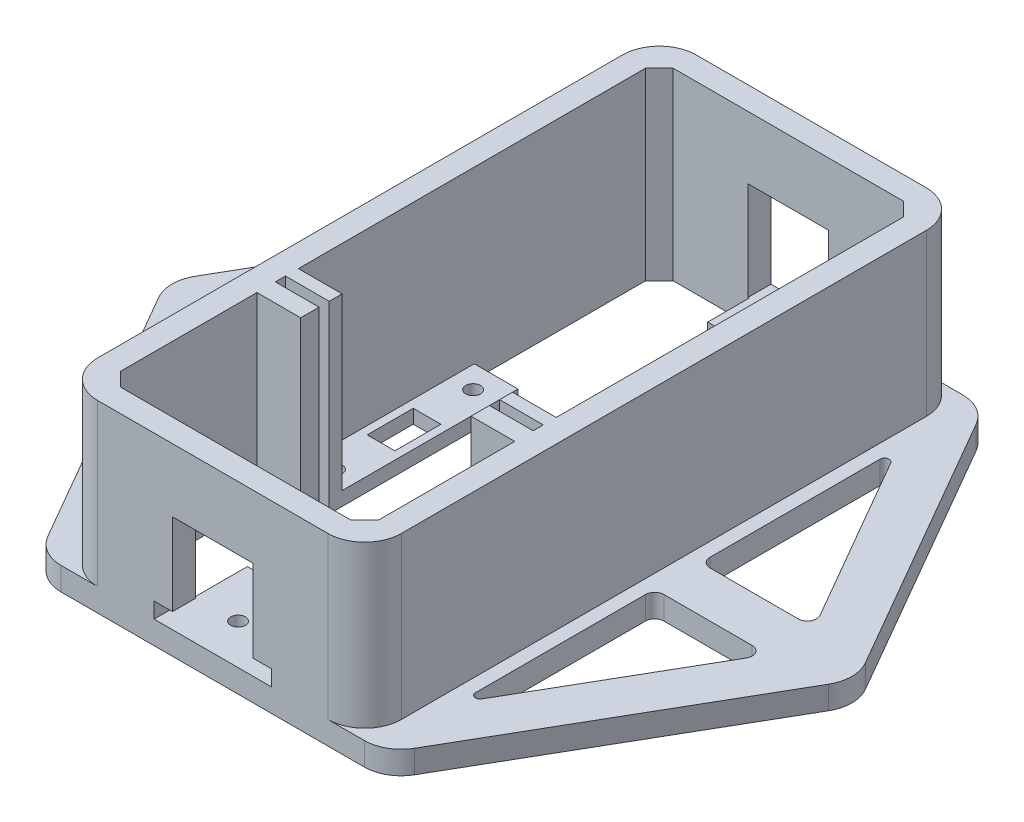
SolidWorks part; units mm, degrees
ref_plane "Front Plane" through (0, 0, 0) normal (0, 0, 1) x (1, 0, 0)
ref_plane "Top Plane" through (0, 0, 0) normal (0, 1, 0) x (1, 0, 0)
ref_plane "Right Plane" through (0, 0, 0) normal (1, 0, 0) x (0, 0, -1)
sketch "Sketch1" plane through (0, 0, 0) normal (0, 1, 0) x (1, 0, 0)
  line L1 (-75.0555, 0) -> (-37.5278, -65)
  line L2 (-37.5278, -65) -> (37.5278, -65)
  line L3 (37.5278, -65) -> (75.0555, 0)
  line L4 (75.0555, 0) -> (37.5278, 65)
  line L5 (37.5278, 65) -> (-37.5278, 65)
  line L6 (-37.5278, 65) -> (-75.0555, 0)
  circle A0 centre (0, 0) radius 65 construction
  circle A1 centre (0, 0) radius 50 construction
  dimension "D2" = 100
  dimension "D1" = 130
extrude "Boss-Extrude1" add sketch "Sketch1" along normal blind 5
fillet "Fillet1" radius 8 6 edges at (37.5278, 2.5, -65) (75.0555, 2.5, 0) (37.5278, 2.5, 65) (-37.5278, 2.5, 65) (-75.0555, 2.5, 0) (-37.5278, 2.5, -65)
sketch "Sketch3" plane through (0, 5, 0) normal (0, 1, 0) x (1, 0, 0)
  line L0 (-32.909, -65) -> (32.909, -65) construction
  line L1 (-25, 65) -> (25, 65)
  line L2 (-33, 57) -> (-33, -57)
  line L3 (-25, -65) -> (25, -65)
  line L4 (33, 57) -> (33, -57)
  line L5 (-33, 65) -> (33, -65) construction
  line L6 (-33, -65) -> (33, 65) construction
  arc A0 (33, 57) -> (25, 65) centre (25, 57) ccw
  arc A1 (33, -57) -> (25, -65) centre (25, -57) cw
  arc A2 (-25, -65) -> (-33, -57) centre (-25, -57) cw
  arc A3 (-25, 65) -> (-33, 57) centre (-25, 57) ccw
  point P0 (0, 0)
  dimension "D1" = 8
  dimension "D2" = 50
extrude "Boss-Extrude2" add sketch "Sketch3" along normal blind 35
sketch "Sketch4" plane through (0, 40, 0) normal (0, 1, 0) x (1, 0, 0)
  line L0 (-28, 57) -> (-25, 60)
  line L1 (25, 60) -> (28, 57)
  line L2 (28, -57) -> (25, -60)
  line L3 (-28, -57) -> (-25, -60)
  line L9 (-25, -60) -> (25, -60)
  line L10 (28, -57) -> (28, 57)
  line L11 (25, 60) -> (-25, 60)
  line L12 (-28, 57) -> (-28, -57)
  line L13 (-25, -60) -> (25, -60)
  line L14 (28, -57) -> (28, 57)
  line L15 (25, 60) -> (-25, 60)
  line L16 (-28, 57) -> (-28, -57)
  arc A9 (-28, -57) -> (-25, -60) centre (-25, -57) ccw
  arc A10 (25, -60) -> (28, -57) centre (25, -57) ccw
  arc A11 (28, 57) -> (25, 60) centre (25, 57) ccw
  arc A12 (-25, 60) -> (-28, 57) centre (-25, 57) ccw
  dimension "D1" = 5
extrude "Cut-Extrude1" cut sketch "Sketch4" against normal up to surface (40 mm away) up to face at (0, 0, 0)
sketch "Sketch8" plane through (0, 0, 0) normal (0, 1, 0) x (1, 0, 0)
  line L0 (0, 40) -> (0, 25) construction
  line L1 (0, 55) -> (0, 65) construction
  line L2 (9.5263, 26.5) -> (24.2487, 52) construction
  line L3 (22.5167, 55) -> (-22.5167, 55) construction
  line L4 (-24.2487, 52) -> (-9.5263, 26.5) construction
  line L5 (-12.5, 0) -> (-62.3346, 0) construction
  line L36 (6.9282, 25) -> (-6.9282, 25) construction
  line L37 (27.7128, 5) -> (57.1577, 5) construction
  line L38 (58.8897, 8) -> (36.3731, 47) construction
  line L39 (32.909, 47) -> (18.1865, 21.5) construction
  line L40 (25.1147, 6.5) -> (18.1865, 18.5) construction
  line L41 (18.1865, -21.5) -> (32.909, -47) construction
  line L42 (36.3731, -47) -> (58.8897, -8) construction
  line L43 (57.1577, -5) -> (27.7128, -5) construction
  line L44 (18.1865, -18.5) -> (25.1147, -6.5) construction
  line L45 (-9.5263, -26.5) -> (-24.2487, -52) construction
  line L46 (-22.5167, -55) -> (22.5167, -55) construction
  line L47 (24.2487, -52) -> (9.5263, -26.5) construction
  line L48 (-6.9282, -25) -> (6.9282, -25) construction
  line L49 (-27.7128, -5) -> (-57.1577, -5) construction
  line L50 (-58.8897, -8) -> (-36.3731, -47) construction
  line L51 (-32.909, -47) -> (-18.1865, -21.5) construction
  line L52 (-25.1147, -6.5) -> (-18.1865, -18.5) construction
  line L53 (-18.1865, 21.5) -> (-32.909, 47) construction
  line L54 (-37.866, 44.4141) -> (-58.8897, 8)
  line L55 (-57.1577, 5) -> (-38, 5)
  line L56 (-18.1865, 18.5) -> (-25.1147, 6.5) construction
  line L57 (-36, 7) -> (-36, 43.9141)
  line L58 (-33, 57) -> (-33, -57) construction
  line L59 (-36, -7) -> (-36, -43.9141)
  line L60 (-36.3731, 47) -> (-36, 47.6462) construction
  line L61 (-36, 5) -> (-27.7128, 5) construction
  line L71 (-33, 57) -> (-33, -57) construction
  line L72 (-57.1577, -5) -> (-38, -5)
  line L73 (-37.866, -44.4141) -> (-58.8897, -8)
  line L74 (37.866, -44.4141) -> (58.8897, -8)
  line L75 (57.1577, -5) -> (38, -5)
  line L76 (36, -7) -> (36, -43.9141)
  line L77 (36, 7) -> (36, 43.9141)
  line L78 (57.1577, 5) -> (38, 5)
  line L79 (37.866, 44.4141) -> (58.8897, 8)
  circle A0 centre (0, 0) radius 12.5 construction
  circle A1 centre (0, 40) radius 15 construction
  arc A3 (-22.5167, 55) -> (-24.2487, 52) centre (-22.5167, 53) ccw
  arc A4 (24.2487, 52) -> (22.5167, 55) centre (22.5167, 53) ccw construction
  arc A5 (6.9282, 25) -> (9.5263, 26.5) centre (6.9282, 28) ccw construction
  arc A6 (-6.9282, 25) -> (-9.5263, 26.5) centre (-6.9282, 28) cw construction
  arc A7 (25.1147, 6.5) -> (27.7128, 5) centre (27.7128, 8) ccw construction
  arc A8 (57.1577, 5) -> (58.8897, 8) centre (57.1577, 7) ccw construction
  arc A9 (36.3731, 47) -> (32.909, 47) centre (34.641, 46) ccw construction
  arc A10 (18.1865, 18.5) -> (18.1865, 21.5) centre (20.7846, 20) cw construction
  arc A11 (18.1865, -18.5) -> (18.1865, -21.5) centre (20.7846, -20) ccw construction
  arc A12 (32.909, -47) -> (36.3731, -47) centre (34.641, -46) ccw construction
  arc A13 (58.8897, -8) -> (57.1577, -5) centre (57.1577, -7) ccw construction
  arc A14 (25.1147, -6.5) -> (27.7128, -5) centre (27.7128, -8) cw construction
  arc A15 (-6.9282, -25) -> (-9.5263, -26.5) centre (-6.9282, -28) ccw construction
  arc A16 (-24.2487, -52) -> (-22.5167, -55) centre (-22.5167, -53) ccw construction
  arc A17 (22.5167, -55) -> (24.2487, -52) centre (22.5167, -53) ccw construction
  arc A18 (6.9282, -25) -> (9.5263, -26.5) centre (6.9282, -28) cw construction
  arc A19 (-25.1147, -6.5) -> (-27.7128, -5) centre (-27.7128, -8) ccw construction
  arc A20 (-57.1577, -5) -> (-58.8897, -8) centre (-57.1577, -7) ccw construction
  arc A21 (-36.3731, -47) -> (-32.909, -47) centre (-34.641, -46) ccw construction
  arc A22 (-18.1865, -18.5) -> (-18.1865, -21.5) centre (-20.7846, -20) cw construction
  arc A23 (-18.1865, 18.5) -> (-18.1865, 21.5) centre (-20.7846, 20) ccw construction
  arc A24 (-32.909, 47) -> (-36.3731, 47) centre (-34.641, 46) ccw construction
  arc A25 (-58.8897, 8) -> (-57.1577, 5) centre (-57.1577, 7) ccw
  arc A26 (-25.1147, 6.5) -> (-27.7128, 5) centre (-27.7128, 8) cw construction
  arc A28 (57.1577, -5) -> (58.8897, -8) centre (57.1577, -7) cw construction
  arc A31 (-36, 7) -> (-38, 5) centre (-38, 7) cw
  arc A32 (-36, 43.9141) -> (-37.866, 44.4141) centre (-37, 43.9141) ccw
  arc A33 (-36, -43.9141) -> (-37.866, -44.4141) centre (-37, -43.9141) cw
  arc A34 (-36, -7) -> (-38, -5) centre (-38, -7) ccw
  arc A35 (-58.8897, -8) -> (-57.1577, -5) centre (-57.1577, -7) cw
  arc A36 (57.1577, -5) -> (58.8897, -8) centre (57.1577, -7) cw construction
  arc A37 (58.8897, -8) -> (57.1577, -5) centre (57.1577, -7) ccw
  arc A38 (36, -7) -> (38, -5) centre (38, -7) cw
  arc A39 (36, -43.9141) -> (37.866, -44.4141) centre (37, -43.9141) ccw
  arc A40 (36, 43.9141) -> (37.866, 44.4141) centre (37, 43.9141) cw
  arc A41 (36, 7) -> (38, 5) centre (38, 7) ccw
  arc A42 (58.8897, 8) -> (57.1577, 5) centre (57.1577, 7) cw
  point P19 (0, 25)
  point P30 (0, 0)
  point P66 (0, 0)
  point P88 (0, 0)
  dimension "D1" = 25
  dimension "D3" = 30
  dimension "D6" = 2
  dimension "D8" = 3
  dimension "D11" = 2
  dimension "D12" = 1
  dimension "D2" = 40
  dimension "D4" = 10
  dimension "D5" = 15
  dimension "D7" = 25
  dimension "D9" = 3
extrude "Cut-Extrude2" cut sketch "Sketch8" along normal up to surface (5 mm away) up to face at (-41.2442, 5, 0)
sketch "Sketch9" plane through (0, 0, 0) normal (0, -1, 0) x (1, 0, 0)
  line L0 (28, 57) -> (28, -57) construction
  line L1 (18.5, 20.1972) -> (28, 20.1972)
  line L2 (18.5, 20.1972) -> (18.5, -19.8028)
  line L3 (18.5, -19.8028) -> (28, -19.8028)
  line L4 (28, 20.1972) -> (28, -19.8028)
  line L5 (18.5, 20.1972) -> (28, -19.8028) construction
  line L6 (18.5, -19.8028) -> (28, 20.1972) construction
  line L7 (0, 0.1972) -> (23.25, 0.1972) construction
  line L8 (0, 0.1972) -> (0, -19.8028) construction
  line L9 (-18.5, -19.8028) -> (-28, -19.8028)
  line L10 (-28, 20.1972) -> (-28, -19.8028)
  line L11 (-18.5, 20.1972) -> (-28, 20.1972)
  line L12 (-18.5, 20.1972) -> (-18.5, -19.8028)
  point P4 (23.25, 0.1972)
  dimension "D1" = 23.25
  dimension "D2" = 40
  dimension "D3" = 9.5
extrude "Boss-Extrude3" add sketch "Sketch9" against normal blind 3
sketch "Sketch10" plane through (0, 3, 0) normal (0, 1, 0) x (1, 0, 0)
  line L0 (23.25, -0.1972) -> (23.25, -15.1972) construction
  line L1 (0, -0.1972) -> (23.25, -0.1972) construction
  line L2 (0, -0.1972) -> (0, 17.7568) construction
  line L3 (0, 0) -> (0, -0.1972) construction
  line L4 (-26.25, -5.1972) -> (-20.25, 4.8028) construction
  line L5 (26.25, 4.8028) -> (20.25, 4.8028)
  line L6 (26.25, 4.8028) -> (26.25, -5.1972)
  line L7 (26.25, -5.1972) -> (20.25, -5.1972)
  line L8 (20.25, 4.8028) -> (20.25, -5.1972)
  line L9 (26.25, 4.8028) -> (20.25, -5.1972) construction
  line L10 (26.25, -5.1972) -> (20.25, 4.8028) construction
  line L11 (-26.25, 4.8028) -> (-20.25, -5.1972) construction
  line L12 (-23.25, -0.1972) -> (-23.25, -15.1972) construction
  line L13 (-20.25, 4.8028) -> (-20.25, -5.1972)
  line L14 (-26.25, -5.1972) -> (-20.25, -5.1972)
  line L15 (-26.25, 4.8028) -> (-26.25, -5.1972)
  line L16 (-26.25, 4.8028) -> (-20.25, 4.8028)
  circle A1 centre (23.25, -15.1972) radius 1.6
  circle A2 centre (23.25, 14.8028) radius 1.6
  circle A3 centre (-23.25, 14.8028) radius 1.6
  circle A4 centre (-23.25, -15.1972) radius 1.6
  dimension "D1" = 23.25
  dimension "D3" = 3.2
  dimension "D2" = 15
  dimension "D4" = 6
  dimension "D5" = 10
extrude "Cut-Extrude3" cut sketch "Sketch10" against normal up to surface (3 mm away) up to face at (44.0289, 0, -18.855)
sketch "Sketch11" plane through (0, 0, 0) normal (0, -1, 0) x (1, 0, 0)
  line L0 (-28, -57) -> (-28, 57) construction
  line L5 (-28, 23.4) -> (-18.5, 23.4)
  line L6 (-18.5, 23.4) -> (-18.5, 27.4)
  line L7 (-28, 20.1972) -> (-28, 21.1972)
  line L8 (-18.5, 20.1972) -> (-28, 20.1972) construction
  line L9 (-28, 20.1972) -> (-18.5, 20.1972) construction
  line L10 (-18.5, -19.8028) -> (-18.5, 20.1972) construction
  line L11 (-28, 20.1972) -> (-28, 18.3944)
  line L12 (-28, 18.3944) -> (-18.5, 18.3944)
  line L13 (-18.5, 18.3944) -> (-18.5, 21.1972)
  line L14 (-18.5, 21.1972) -> (-28, 21.1972)
  line L15 (-28, 21.1972) -> (-28, 23.4) construction
  line L16 (-18.5, 27.4) -> (-28, 27.4)
  line L17 (-28, 27.4) -> (-28, 23.4)
  line L18 (0, 0) -> (0, 78.4152) construction
  line L19 (28, 21.1972) -> (28, 23.4) construction
  line L20 (28, 20.1972) -> (18.5, 20.1972) construction
  line L21 (28, 27.4) -> (28, 23.4)
  line L22 (18.5, 27.4) -> (28, 27.4)
  line L23 (18.5, 21.1972) -> (28, 21.1972)
  line L24 (18.5, 18.3944) -> (18.5, 21.1972)
  line L25 (28, 18.3944) -> (18.5, 18.3944)
  line L26 (28, 20.1972) -> (28, 18.3944)
  line L27 (28, 20.1972) -> (28, 21.1972)
  line L28 (18.5, 23.4) -> (18.5, 27.4)
  line L29 (28, 23.4) -> (18.5, 23.4)
  dimension "D1" = 4
  dimension "D3" = 1
  dimension "D4" = 1.8028
  dimension "D5" = 2.2028
extrude "Boss-Extrude4" add sketch "Sketch11" against normal up to surface (40 mm away) up to face at (0, 40, 0)
sketch "Sketch13" plane through (0, 0, 60) normal (0, 0, -1) x (-1, 0, 0)
  line L0 (0, 0) -> (0, 5) construction
  line L1 (-25, 0) -> (25, 0) construction
  line L2 (0, 0) -> (12.5, 5) construction
  line L3 (12.5, 5) -> (12.5, 0)
  line L4 (12.5, 0) -> (-12.5, 0)
  line L5 (12.5, 5) -> (-12.5, 5)
  line L6 (0, 0) -> (-12.5, 5) construction
  line L7 (-12.5, 5) -> (-12.5, 0)
  dimension "D1" = 12.5
extrude "Boss-Extrude5" add sketch "Sketch13" along normal up to surface (15 mm away)
sketch "Sketch15" plane through (0, 0, 0) normal (0, -1, 0) x (1, 0, 0)
  line L0 (12.5, 45) -> (12.5, 52.5) construction
  line L1 (12.5, 48.75) -> (-12.5, 48.75) construction
  line L2 (12.5, 48.75) -> (3.25, 48.75) construction
  line L3 (0, 45) -> (0, 60) construction
  line L4 (12.5, 45) -> (12.5, 48.75)
  line L5 (-12.5, 45) -> (-12.5, 52.5) construction
  line L6 (-12.5, 52.5) -> (12.5, 52.5) construction
  circle A0 centre (3.25, 48.75) radius 1.6
  circle A1 centre (-3.25, 48.75) radius 1.6
  circle A2 centre (-3.25, 56.25) radius 1.6
  circle A3 centre (3.25, 56.25) radius 1.6
  circle A4 centre (-3.25, 48.75) radius 3 construction
  dimension "D2" = 3.2
  dimension "D1" = 3.75
extrude "Cut-Extrude4" cut sketch "Sketch15" against normal blind 5 contours A0 | A3 | A1 | A2
sketch "Sketch16" plane through (0, 0, 65) normal (0, 0, 1) x (1, 0, 0)
  line L0 (0, 0) -> (0, 5) construction
  line L1 (-32.909, 0) -> (32.909, 0) construction
  line L2 (-12.75, 5) -> (12.75, 5)
  line L3 (-12.75, 5) -> (-12.75, 8.4)
  line L4 (12.75, 5) -> (12.75, 7.5183)
  line L5 (-12.75, 8.4) -> (-8.75, 8.4)
  line L6 (-8.75, 8.4) -> (-8.75, 26.25)
  line L7 (-8.75, 26.25) -> (8.75, 26.25)
  line L8 (8.75, 8.4) -> (8.75, 26.25)
  line L9 (12.75, 8.4) -> (8.75, 8.4)
  line L10 (12.75, 5) -> (12.75, 8.4)
  point P7 (0, 5)
  point P13 (0, 26.25)
  dimension "D1" = 5
  dimension "D2" = 4
  dimension "D3" = 3.4
  dimension "D4" = 12.75
  dimension "D5" = 17.85
  dimension "D6" = 8.75
extrude "Cut-Extrude5" cut sketch "Sketch16" against normal up to surface (5 mm away) contours L2 L3 L5 L6 L7 L8 L9 L10 up to face at (0, 11.25, 60)
sketch "Sketch17" plane through (0, 0, -60) normal (0, 0, 1) x (1, 0, 0)
  line L0 (0, 0) -> (-8.5, 0) construction
  line L1 (-25, 0) -> (25, 0) construction
  line L3 (-8.5, 0) -> (8.5, 0)
  line L4 (-8.5, 0) -> (-8.5, 5)
  line L5 (-8.5, 5) -> (8.5, 5)
  line L6 (8.5, 0) -> (8.5, 5)
  line L7 (-8.5, 0) -> (8.5, 5) construction
  line L8 (-8.5, 5) -> (8.5, 0) construction
  point P7 (0, 2.5)
  dimension "D1" = 5
  dimension "D2" = 17
extrude "Boss-Extrude6" add sketch "Sketch17" along normal blind 9
sketch "Sketch18" plane through (0, 0, 0) normal (0, -1, 0) x (1, 0, 0)
  line L0 (0, -51) -> (0, -66) construction
  line L1 (8.5, -51) -> (-8.5, -51) construction
  line L2 (-8.5, -51) -> (8.5, -51) construction
  line L3 (3.25, -54.75) -> (3.25, -51) construction
  line L4 (3.25, -54.75) -> (8.5, -54.75) construction
  line L5 (-8.5, -51) -> (8.5, -51) construction
  line L6 (-8.5, -51) -> (8.5, -51) construction
  circle A0 centre (-3.25, -54.75) radius 1.6
  circle A1 centre (3.25, -54.75) radius 1.6
  circle A2 centre (3.25, -54.75) radius 3 construction
extrude "Cut-Extrude6" cut sketch "Sketch18" against normal blind 5
sketch "Sketch19" plane through (0, 0, -65) normal (0, 0, -1) x (-1, 0, 0)
  line L0 (0, 0) -> (0, 5) construction
  line L1 (-8.5, 5) -> (8.5, 5) construction
  line L9 (0, 5) -> (-8.75, 5)
  line L10 (-8.75, 5) -> (-8.75, 26.4)
  line L11 (-8.75, 26.4) -> (8.75, 26.4)
  line L12 (8.75, 5) -> (8.75, 26.4)
  line L13 (0, 5) -> (8.75, 5)
  point P8 (0, 26.4)
  dimension "D1" = 8.75
  dimension "D2" = 21.4
extrude "Cut-Extrude8" cut sketch "Sketch19" against normal blind 5
